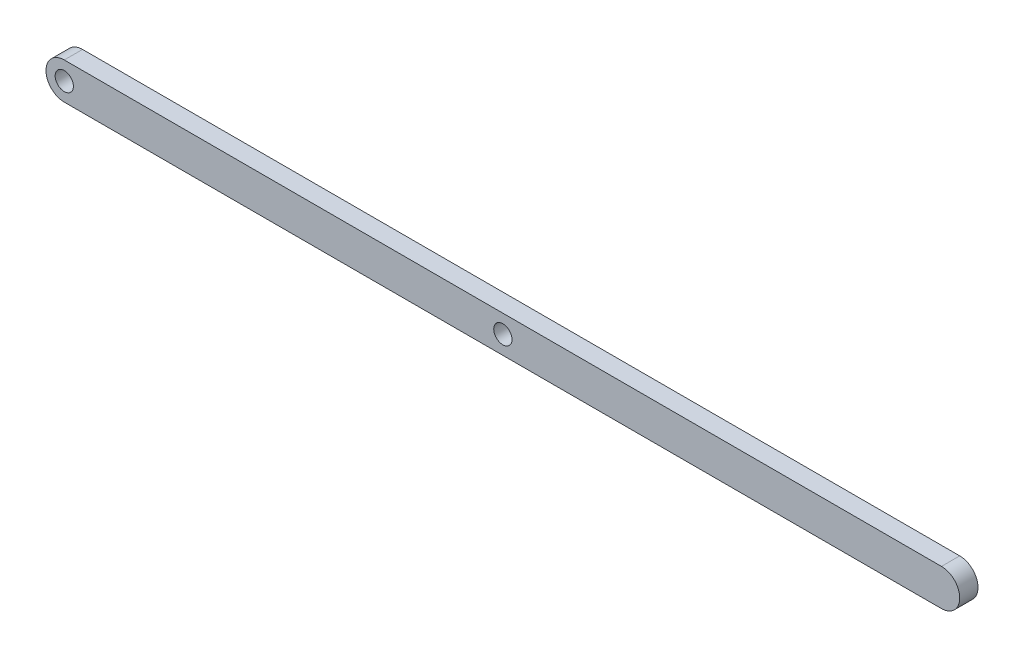
SolidWorks part; units mm, degrees
ref_plane "Front Plane" through (0, 0, 0) normal (0, 0, 1) x (1, 0, 0)
ref_plane "Top Plane" through (0, 0, 0) normal (0, 1, 0) x (1, 0, 0)
ref_plane "Right Plane" through (0, 0, 0) normal (1, 0, 0) x (0, 0, -1)
sketch "Sketch1" plane through (0, 0, 0) normal (0, 0, 1) x (1, 0, 0)
  line L0 (-152.4, 0) -> (152.4, 0) construction
  line L1 (-152.4, 6.35) -> (152.4, 6.35)
  line L2 (-152.4, -6.35) -> (152.4, -6.35)
  arc A0 (-152.4, 6.35) -> (-152.4, -6.35) centre (-152.4, 0) ccw
  arc A1 (152.4, -6.35) -> (152.4, 6.35) centre (152.4, 0) ccw
  circle A3 centre (-152.4, 0) radius 3.175
  circle A4 centre (0, 0) radius 3.175
  point P2 (0, 0)
  dimension "D1" = 6.35
  dimension "D3" = 6.35
  dimension "D2" = 304.8
extrude "Boss-Extrude1" add sketch "Sketch1" along normal blind 6.35
